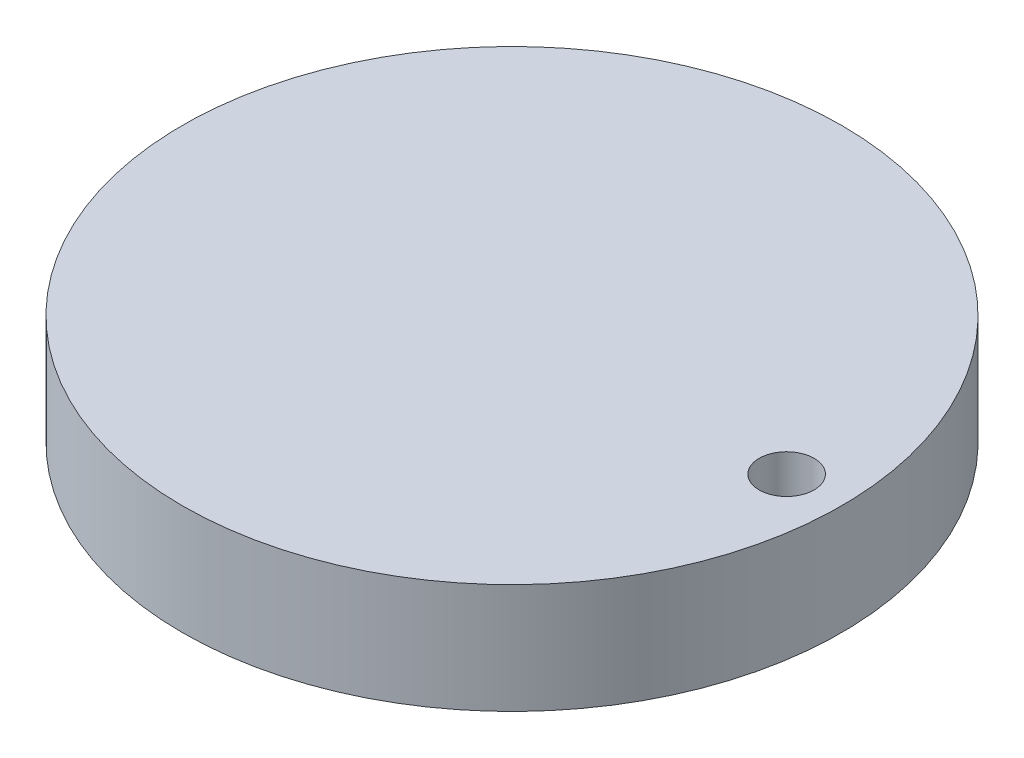
SolidWorks part; units mm, degrees
ref_plane "Front Plane" through (0, 0, 0) normal (0, 0, 1) x (1, 0, 0)
ref_plane "Top Plane" through (0, 0, 0) normal (0, 1, 0) x (1, 0, 0)
ref_plane "Right Plane" through (0, 0, 0) normal (1, 0, 0) x (0, 0, -1)
sketch "Sketch1" plane through (0, 0, 0) normal (0, 1, 0) x (1, 0, 0)
  circle A0 centre (0, 0) radius 30
  dimension "D1" = 60
extrude "Boss-Extrude1" add sketch "Sketch1" along normal blind 10
sketch "Sketch2" plane through (0, 0, 0) normal (0, -1, 0) x (1, 0, 0)
  circle A0 centre (0, 0) radius 4.25
  dimension "D1" = 8.5
extrude "Cut-Extrude1" cut sketch "Sketch2" against normal blind 7
sketch "Sketch3" plane through (0, 10, 0) normal (0, 1, 0) x (1, 0, 0)
  arc A0 (24.875, 2.4969) -> (24.875, -2.4969) centre (0, 0) ccw
  circle A1 centre (25, 0) radius 2.5
  dimension "D1" = 50
  dimension "D2" = 5
extrude "Cut-Extrude2" cut sketch "Sketch3" against normal blind 6 from surface at 0 contours A1 starting at face at (0, 10, 30)
